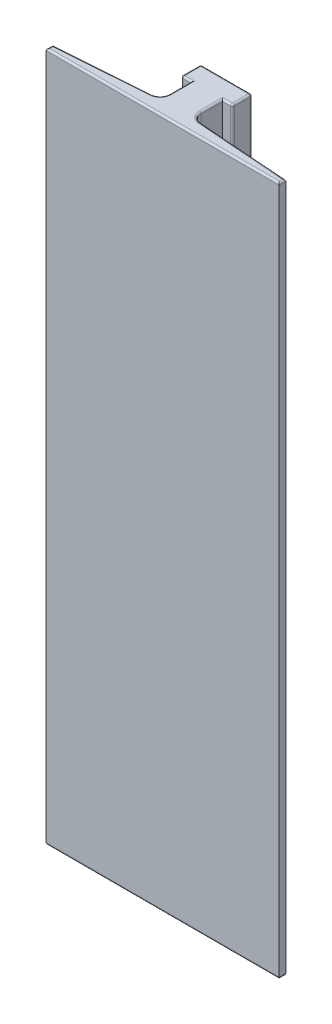
SolidWorks part; units mm, degrees
ref_plane "Front" through (0, 0, 0) normal (0, 0, 1) x (1, 0, 0)
ref_plane "Top" through (0, 0, 0) normal (0, 1, 0) x (1, 0, 0)
ref_plane "Right" through (0, 0, 0) normal (1, 0, 0) x (0, 0, -1)
sketch "Sketch4" plane through (0, 0, 0) normal (0, 1, 0) x (1, 0, 0)
  line L3 (2.2633, 4.4182) -> (2.2633, 1.1782)
  line L5 (-1.1367, 4.4182) -> (-1.1367, 1.1782)
  line L6 (-11.9367, 0.3882) -> (-1.1367, 1.1782)
  line L7 (-1.1367, 1.1782) -> (-1.1367, -0.3218) construction
  line L8 (2.2633, 1.1782) -> (2.2633, -0.3218) construction
  line L9 (-1.1367, 4.4182) -> (-2.1867, 4.4182)
  line L10 (3.3133, 6.5182) -> (-2.1867, 6.5182)
  line L11 (3.3133, 6.5182) -> (3.3133, 4.4182)
  line L12 (3.3133, 4.4182) -> (2.2633, 4.4182)
  line L13 (-2.1867, 6.5182) -> (-2.1867, 4.4182)
  line L14 (2.2633, 1.1782) -> (13.0633, 0.3882)
  line L16 (13.0633, 0.3882) -> (13.0633, -0.3218)
  line L17 (13.0633, -0.3218) -> (-11.9367, -0.3218)
  line L18 (-11.9367, 0.3882) -> (-11.9367, -0.3218)
  point P0 (0.5633, 0.2155)
  dimension "D1" = 3.4
  dimension "D2" = 0.71
  dimension "D3" = 5.5
  dimension "D4" = 2.1
  dimension "D5" = 1.5
  dimension "D6" = 25
  dimension "D7" = 0.71
  dimension "D8" = 3.24
extrude "Boss-Extrude1" add sketch "Sketch4" along normal blind 74 contours L5 L6 L18 L17 L16 L14 L3 L12 L11 L10 L13 L9
fillet "Fillet2" radius 1 2 edges at (2.2633, 37, -1.1782) (-1.1367, 37, -1.1782)
fillet "Fillet3" radius 0.2 32 edges at (-2.1867, 37, -4.4182) (-2.1867, 37, -6.5182) (3.3133, 37, -4.4182) (3.3133, 37, -6.5182) (-1.1367, 0, -3.2629) (-1.4042, 0, -1.4269) (-7.0002, 0, -0.7493) (-11.9367, 0, -0.0332) (0.5633, 0, 0.3218) (13.0633, 0, -0.0332) (8.1269, 0, -0.7493) (2.5309, 0, -1.4269) (2.2633, 0, -3.2629) (2.7883, 0, -4.4182) (3.3133, 0, -5.4682) (0.5633, 0, -6.5182) (-2.1867, 0, -5.4682) (-1.6617, 0, -4.4182) (-2.1867, 74, -5.4682) (0.5633, 74, -6.5182) (3.3133, 74, -5.4682) (2.7883, 74, -4.4182) (2.2633, 74, -3.2629) (2.5309, 74, -1.4269) (8.1269, 74, -0.7493) (13.0633, 74, -0.0332) (0.5633, 74, 0.3218) (-11.9367, 74, -0.0332) (-7.0002, 74, -0.7493) (-1.4042, 74, -1.4269) (-1.1367, 74, -3.2629) (-1.6617, 74, -4.4182)
